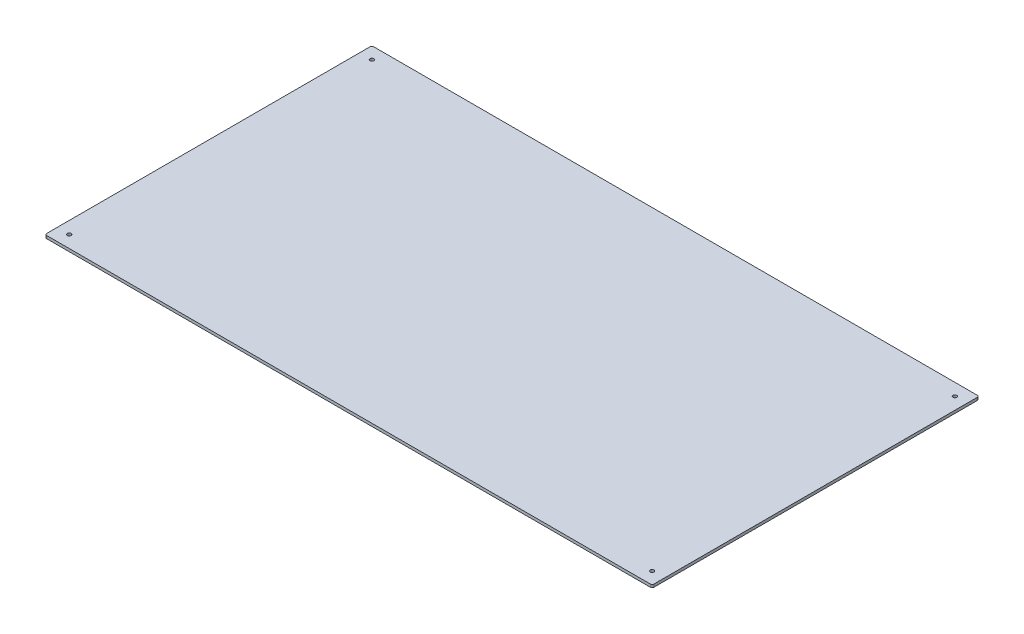
SolidWorks part; units mm, degrees
ref_plane "前视基准面" through (0, 0, 0) normal (0, 0, 1) x (1, 0, 0)
ref_plane "上视基准面" through (0, 0, 0) normal (0, 1, 0) x (1, 0, 0)
ref_plane "右视基准面" through (0, 0, 0) normal (1, 0, 0) x (0, 0, -1)
sketch "草图1" plane through (0, 0, 0) normal (0, 1, 0) x (1, 0, 0)
  line L1 (2, 0) -> (648, 0)
  line L2 (0, 2) -> (0, 348)
  line L3 (2, 350) -> (648, 350)
  line L4 (650, 2) -> (650, 348)
  arc A0 (648, 350) -> (650, 348) centre (648, 348) cw
  arc A1 (648, 0) -> (650, 2) centre (648, 2) ccw
  arc A2 (2, 0) -> (0, 2) centre (2, 2) cw
  arc A3 (2, 350) -> (0, 348) centre (2, 348) ccw
  circle A4 centre (13, 13) radius 2
  circle A5 centre (637, 13) radius 2
  circle A6 centre (13, 337) radius 2
  circle A7 centre (637, 337) radius 2
  point P9 (650, 0)
  point P12 (0, 0)
  point P15 (0, 350)
  dimension "D3" = 2
  dimension "D4" = 4
  dimension "D7" = 4
  dimension "D10" = 4
  dimension "D13" = 4
  dimension "D1" = 350
  dimension "D2" = 650
  dimension "D5" = 13
  dimension "D6" = 13
  dimension "D8" = 13
  dimension "D9" = 13
  dimension "D11" = 13
  dimension "D12" = 13
  dimension "D14" = 13
  dimension "D15" = 13
extrude "凸台-拉伸1" add sketch "草图1" along normal blind 3
